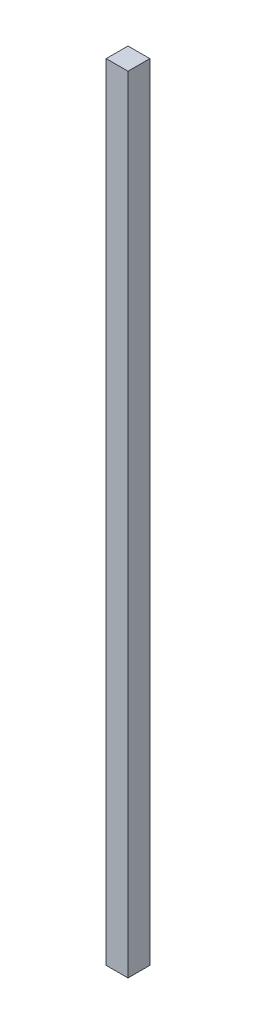
SolidWorks part; units mm, degrees
ref_plane "Front Plane" through (0, 0, 0) normal (0, 0, 1) x (1, 0, 0)
ref_plane "Top Plane" through (0, 0, 0) normal (0, 1, 0) x (1, 0, 0)
ref_plane "Right Plane" through (0, 0, 0) normal (1, 0, 0) x (0, 0, -1)
sketch "Sketch1" plane through (0, 0, 0) normal (1, 0, 0) x (0, 0, -1)
  line L1 (12.7, -457.2) -> (-12.7, -457.2)
  line L2 (12.7, -457.2) -> (12.7, 457.2)
  line L3 (12.7, 457.2) -> (-12.7, 457.2)
  line L4 (-12.7, -457.2) -> (-12.7, 457.2)
  line L5 (12.7, -457.2) -> (-12.7, 457.2) construction
  line L6 (12.7, 457.2) -> (-12.7, -457.2) construction
  point P0 (0, 0)
  dimension "D1" = 914.4
  dimension "D2" = 25.4
extrude "Boss-Extrude1" add sketch "Sketch1" along normal blind 25.4
